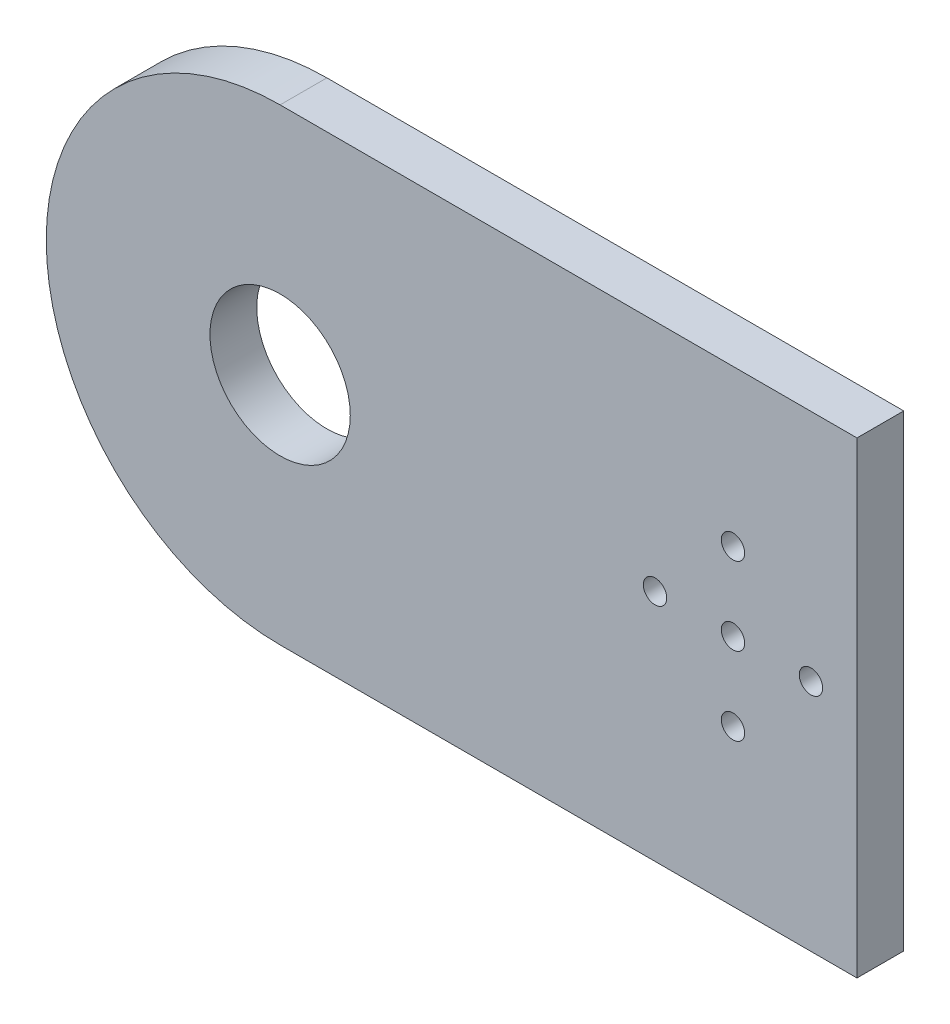
SolidWorks part; units mm, degrees
material "Aleación 1060"
ref_plane "Alzado" through (0, 0, 0) normal (0, 0, 1) x (1, 0, 0)
ref_plane "Planta" through (0, 0, 0) normal (0, 1, 0) x (1, 0, 0)
ref_plane "Vista lateral" through (0, 0, 0) normal (1, 0, 0) x (0, 0, -1)
sketch "Croquis1" plane through (0, 0, 0) normal (0, 0, 1) x (1, 0, 0)
  line L1 (-37, 30) -> (37, 30)
  line L3 (-37, -30) -> (37, -30)
  line L4 (37, 30) -> (37, -30)
  line L5 (-37, 30) -> (37, -30) construction
  line L6 (-37, -30) -> (37, 30) construction
  arc A0 (-37, 30) -> (-37, -30) centre (-37, 0) ccw
  point P0 (0, 0)
  dimension "D2" = 30
  dimension "D1" = 74
extrude "Saliente-Extruir1" add sketch "Croquis1" along normal blind 6
sketch "Croquis2" plane through (0, 0, 6) normal (0, 0, 1) x (1, 0, 0)
  circle A0 centre (21.0941, -10) radius 1.5
  circle A1 centre (21.0941, 0) radius 1.5
  circle A2 centre (21.0941, 10) radius 1.5
  circle A3 centre (31.0941, 0) radius 1.5
  circle A4 centre (11.0941, 0) radius 1.5
  dimension "D1" = 3
extrude "Cortar-Extruir1" cut sketch "Croquis2" against normal through all
sketch "Croquis3" plane through (0, 0, 6) normal (0, 0, 1) x (1, 0, 0)
  circle A0 centre (-37, 0) radius 9
  dimension "D1" = 18
extrude "Cortar-Extruir2" cut sketch "Croquis3" against normal through all
